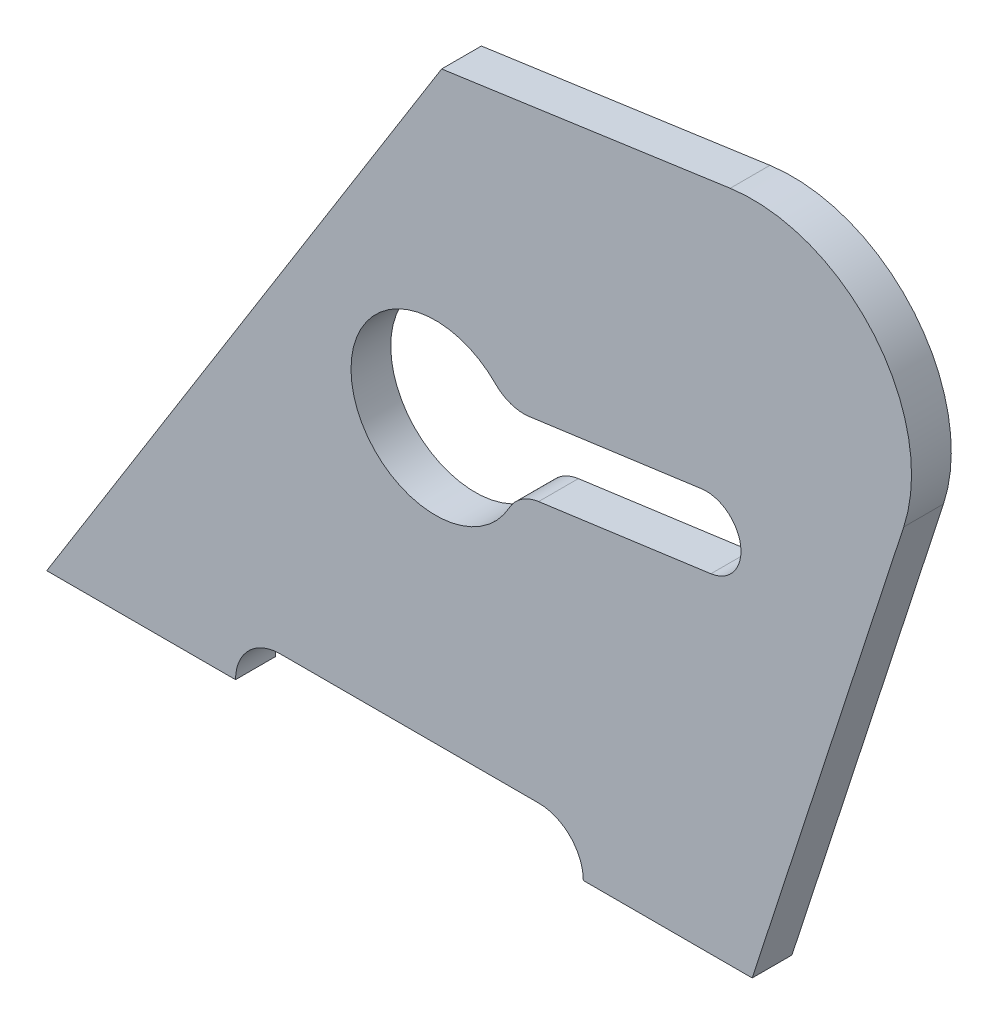
SolidWorks part; units mm, degrees
ref_plane "Front Plane" through (0, 0, 0) normal (0, 0, 1) x (1, 0, 0)
ref_plane "Top Plane" through (0, 0, 0) normal (0, 1, 0) x (1, 0, 0)
ref_plane "Right Plane" through (0, 0, 0) normal (1, 0, 0) x (0, 0, -1)
sketch "Sketch1" plane through (0, 0, 0) normal (0, 0, 1) x (1, 0, 0)
  line L0 (0, 0) -> (79.4879, 127.2072)
  line L1 (79.4879, 127.2072) -> (137.573, 135.4513)
  line L2 (172.5035, 93.8803) -> (142, 0)
  line L3 (55, 0) -> (-55, 0) construction
  line L4 (142, 0) -> (108, 0)
  line L5 (99, 9) -> (47, 9)
  line L6 (38, 0) -> (0, 0)
  line L7 (37.6243, 60.2114) -> (167.3394, 77.9866) construction
  line L8 (131.7851, 80.1799) -> (97.1091, 75.4282)
  line L9 (133.6858, 66.3096) -> (99.0098, 61.5578)
  line L10 (131.7851, 80.1799) -> (132.7354, 73.2448) construction
  line L11 (132.7354, 73.2448) -> (133.6858, 66.3096) construction
  line L12 (96.023, 83.3541) -> (98.0595, 68.493) construction
  line L13 (100.0959, 53.6319) -> (98.0595, 68.493) construction
  arc A0 (108, 0) -> (99, 9) centre (99, 0) ccw
  arc A1 (47, 9) -> (38, 0) centre (47, 0) ccw
  arc A2 (172.5035, 93.8803) -> (137.573, 135.4513) centre (142.0697, 103.7688) ccw
  arc A3 (90.3339, 77.7297) -> (93.1035, 57.5186) centre (78.2447, 65.7777) ccw
  arc A5 (90.3339, 77.7297) -> (97.1091, 75.4282) centre (96.023, 83.3541) ccw
  arc A6 (99.0098, 61.5578) -> (93.1035, 57.5186) centre (100.0959, 53.6319) ccw
  arc A7 (131.7851, 80.1799) -> (133.6858, 66.3096) centre (132.7354, 73.2448) cw
  point P15 (188.3525, 142.6585)
  point P16 (37.6243, 60.2114)
  point P17 (167.3394, 77.9866)
  dimension "D8" = 32
  dimension "D13" = 34
  dimension "D14" = 7
  dimension "D16" = 16
  dimension "D17" = 16
  dimension "D18" = 7
  dimension "D1" = 58
  dimension "D2" = 47
  dimension "D3" = 52
  dimension "D4" = 108
  dimension "D5" = 150
  dimension "D6" = 150
  dimension "D7" = 142
  dimension "D9" = 9
  dimension "D10" = 82
  dimension "D11" = 71
  dimension "D12" = 41
  dimension "D15" = 55
extrude "Boss-Extrude1" add sketch "Sketch1" along normal blind 8
